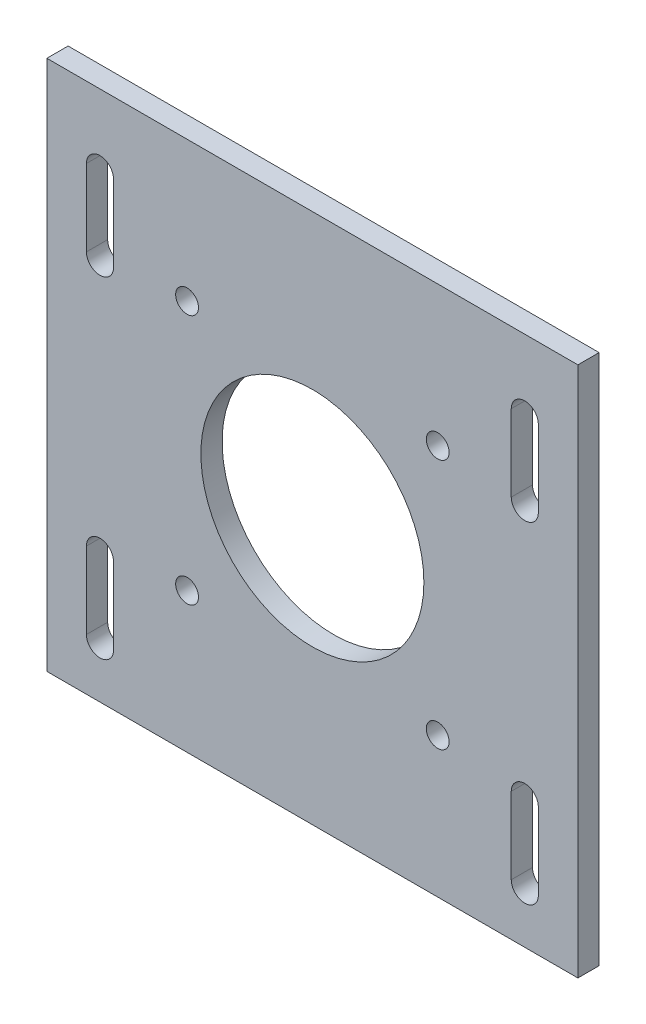
SolidWorks part; units mm, degrees
ref_plane "Front Plane" through (0, 0, 0) normal (0, 0, 1) x (1, 0, 0)
ref_plane "Top Plane" through (0, 0, 0) normal (0, 1, 0) x (1, 0, 0)
ref_plane "Right Plane" through (0, 0, 0) normal (1, 0, 0) x (0, 0, -1)
sketch "Sketch1" plane through (0, 0, 0) normal (0, 0, 1) x (1, 0, 0)
  line L0 (50, 40) -> (50, 51.0991) construction
  line L2 (0, 0) -> (0, 90)
  line L3 (0, 90) -> (100, 90)
  line L4 (100, 2.3723) -> (100, 90)
  line L7 (10, 14.1724) -> (10, -0.2503) construction
  line L10 (90, 14.1724) -> (90, -0.2503) construction
  line L13 (7.45, 14.1724) -> (7.45, -0.2503)
  line L16 (0, 0) -> (0, -10)
  line L17 (0, -10) -> (100, -10)
  line L18 (100, -10) -> (100, 2.3723)
  line L20 (90, 62.1506) -> (90, 76.5733) construction
  line L21 (87.45, 62.1506) -> (87.45, 76.5733)
  line L22 (92.55, 62.1506) -> (92.55, 76.5733)
  line L23 (92.55, 14.1724) -> (92.55, -0.2503)
  line L24 (87.45, 14.1724) -> (87.45, -0.2503)
  line L25 (12.55, 14.1724) -> (12.55, -0.2503)
  line L26 (10, 62.1506) -> (10, 76.5733) construction
  line L27 (12.55, 62.1506) -> (12.55, 76.5733)
  line L28 (7.45, 62.1506) -> (7.45, 76.5733)
  circle A8 centre (26.4, 63.6) radius 2.15
  circle A9 centre (73.6, 63.6) radius 2.15
  circle A10 centre (73.6, 16.4) radius 2.15
  circle A11 centre (26.4, 16.4) radius 2.15
  circle A12 centre (50, 40) radius 21
  arc A13 (87.45, 62.1506) -> (92.55, 62.1506) centre (90, 62.1506) ccw
  arc A14 (92.55, 76.5733) -> (87.45, 76.5733) centre (90, 76.5733) ccw
  arc A15 (92.55, 14.1724) -> (87.45, 14.1724) centre (90, 14.1724) ccw
  arc A16 (87.45, -0.2503) -> (92.55, -0.2503) centre (90, -0.2503) ccw
  arc A17 (7.45, 14.1724) -> (12.55, 14.1724) centre (10, 14.1724) cw
  arc A18 (12.55, -0.2503) -> (7.45, -0.2503) centre (10, -0.2503) cw
  arc A19 (12.55, 62.1506) -> (7.45, 62.1506) centre (10, 62.1506) cw
  arc A20 (7.45, 76.5733) -> (12.55, 76.5733) centre (10, 76.5733) cw
  point P8 (10, 6.9611)
  point P15 (10, 69.3619)
  point P21 (90, 6.9611)
  point P33 (50, 40)
  point P48 (90, 69.3619)
  dimension "D9" = 2.55
  dimension "D19" = 4.3
  dimension "D20" = 4.3
  dimension "D21" = 4.3
  dimension "D22" = 4.3
  dimension "D23" = 42
  dimension "D8" = 2.55
  dimension "D2" = 100
  dimension "D3" = 50
  dimension "D4" = 10
  dimension "D7" = 100
  dimension "D11" = 14.4227
  dimension "D12" = 10
  dimension "D17" = 47.2
  dimension "D18" = 47.2
extrude "Boss-Extrude1" add sketch "Sketch1" along normal blind 4
